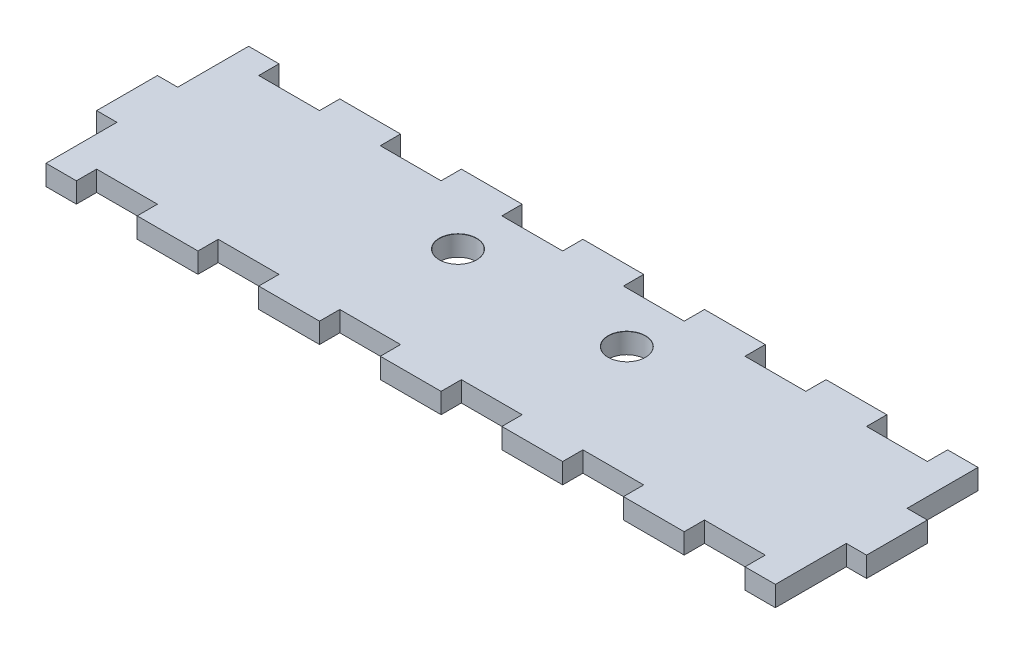
SolidWorks part; units mm, degrees
ref_plane "Front Plane" through (0, 0, 0) normal (0, 0, 1) x (1, 0, 0)
ref_plane "Top Plane" through (0, 0, 0) normal (0, 1, 0) x (1, 0, 0)
ref_plane "Right Plane" through (0, 0, 0) normal (1, 0, 0) x (0, 0, -1)
sketch "Sketch1" plane through (0, 0, 0) normal (0, 1, 0) x (1, 0, 0)
  line L64 (54, 15) -> (49.5, 15)
  line L65 (49.5, 15) -> (49.5, 12)
  line L66 (49.5, 12) -> (40.5, 12)
  line L67 (40.5, 12) -> (40.5, 15)
  line L68 (40.5, 15) -> (31.5, 15)
  line L69 (31.5, 15) -> (31.5, 12)
  line L70 (31.5, 12) -> (22.5, 12)
  line L71 (22.5, 12) -> (22.5, 15)
  line L72 (22.5, 15) -> (13.5, 15)
  line L73 (13.5, 15) -> (13.5, 12)
  line L74 (13.5, 12) -> (4.5, 12)
  line L75 (4.5, 12) -> (4.5, 15)
  line L76 (4.5, 15) -> (-4.5, 15)
  line L77 (-4.5, 15) -> (-4.5, 12)
  line L78 (-4.5, 12) -> (-13.5, 12)
  line L79 (-13.5, 12) -> (-13.5, 15)
  line L80 (-13.5, 15) -> (-22.5, 15)
  line L81 (-22.5, 15) -> (-22.5, 12)
  line L82 (-22.5, 12) -> (-31.5, 12)
  line L83 (-31.5, 12) -> (-31.5, 15)
  line L84 (-31.5, 15) -> (-40.5, 15)
  line L85 (-40.5, 15) -> (-40.5, 12)
  line L86 (-40.5, 12) -> (-49.5, 12)
  line L87 (-49.5, 12) -> (-49.5, 15)
  line L88 (-49.5, 15) -> (-54, 15)
  line L89 (-54, 15) -> (-54, 12)
  line L90 (-54, 12) -> (-54, 4.5)
  line L91 (-54, 4.5) -> (-57, 4.5)
  line L92 (-57, 4.5) -> (-57, -4.5)
  line L93 (-57, -4.5) -> (-54, -4.5)
  line L94 (-54, -4.5) -> (-54, -12)
  line L95 (-54, -12) -> (-54, -15)
  line L96 (-54, -15) -> (-49.5, -15)
  line L97 (-49.5, -15) -> (-49.5, -12)
  line L98 (-49.5, -12) -> (-40.5, -12)
  line L99 (-40.5, -12) -> (-40.5, -15)
  line L100 (-40.5, -15) -> (-31.5, -15)
  line L101 (-31.5, -15) -> (-31.5, -12)
  line L102 (-31.5, -12) -> (-22.5, -12)
  line L103 (-22.5, -12) -> (-22.5, -15)
  line L104 (-22.5, -15) -> (-13.5, -15)
  line L105 (-13.5, -15) -> (-13.5, -12)
  line L106 (-13.5, -12) -> (-4.5, -12)
  line L107 (-4.5, -12) -> (-4.5, -15)
  line L108 (-4.5, -15) -> (4.5, -15)
  line L109 (4.5, -15) -> (4.5, -12)
  line L110 (4.5, -12) -> (13.5, -12)
  line L111 (13.5, -12) -> (13.5, -15)
  line L112 (13.5, -15) -> (22.5, -15)
  line L113 (22.5, -15) -> (22.5, -12)
  line L114 (22.5, -12) -> (31.5, -12)
  line L115 (31.5, -12) -> (31.5, -15)
  line L116 (31.5, -15) -> (40.5, -15)
  line L117 (40.5, -15) -> (40.5, -12)
  line L118 (40.5, -12) -> (49.5, -12)
  line L119 (49.5, -12) -> (49.5, -15)
  line L120 (49.5, -15) -> (54, -15)
  line L121 (54, -15) -> (54, -12)
  line L122 (54, -12) -> (54, -4.5)
  line L123 (54, -4.5) -> (57, -4.5)
  line L124 (57, -4.5) -> (57, 4.5)
  line L125 (57, 4.5) -> (54, 4.5)
  line L126 (54, 4.5) -> (54, 12)
  line L127 (54, 12) -> (54, 15)
  line L898 (-57, 4.5) -> (-57, 15) construction
  line L899 (-57, 15) -> (-54, 15) construction
  line L900 (57, -4.5) -> (57, -15) construction
  line L901 (57, -15) -> (54, -15) construction
  line L902 (-57, 15) -> (57, -15) construction
  point P64 (0, 0)
extrude "Boss-Extrude1" add sketch "Sketch1" along normal mid plane 3
sketch "Sketch2" plane through (0, 1.5, 0) normal (0, 1, 0) x (1, 0, 0)
  text T0 "Front/Back\r\n"
extrude "Cut-Extrude1" [suppressed] cut sketch "Sketch2" against normal blind 1
sketch "Sketch3" plane through (0, 1.5, 0) normal (0, 1, 0) x (1, 0, 0)
  line L0 (0, 30.7048) -> (0, -37.528) construction
  line L1 (-12.5, 4.5) -> (12.5, 4.5) construction
  line L3 (-31.5, 15) -> (-40.5, 15) construction
  point P3 (-12.5, 4.5)
  point P4 (12.5, 4.5)
  point P9 (12.5, 4.5)
  point P10 (-12.5, 4.5)
  point P11 (0, 4.5)
  dimension "D1" = 25
  dimension "D3" = 10.5
hole_wizard "M5 Clearance Hole1" positions "Sketch3" profile "Sketch4" hole size "M5" standard "ISO" end condition through all
sketch "Sketch4" plane through (-12.5, 1.5, -4.5) normal (1, 0, 0) x (0, 0, 1)
  line L0 (0, 0) -> (0, 3)
  line L1 (0, 3) -> (2.75, 3)
  line L2 (2.75, 3) -> (2.75, 0.025)
  line L3 (2.75, 0.025) -> (2.775, 0)
  line L5 (2.775, 0) -> (0, 0)
  line L6 (-2.75, 0.025) -> (-2.775, 0) construction
  line L11 (0, -6.35) -> (0, 107.95) construction
  dimension "Thru Hole Dia." = 5.5
  dimension "Thru Hole Depth" = 3
  dimension "Near C'Sink Dia." = 5.55
  dimension "Near C'Sink Angle" = 90
